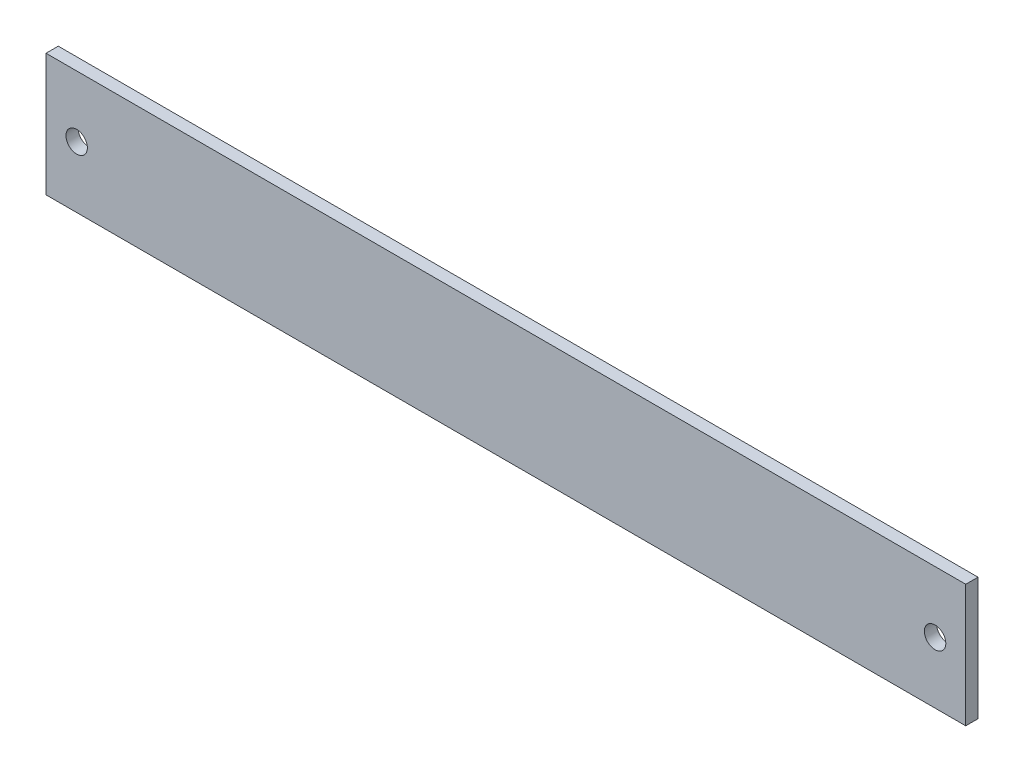
SolidWorks part; units mm, degrees
ref_plane "Front Plane" through (0, 0, 0) normal (0, 0, 1) x (1, 0, 0)
ref_plane "Top Plane" through (0, 0, 0) normal (0, 1, 0) x (1, 0, 0)
ref_plane "Right Plane" through (0, 0, 0) normal (1, 0, 0) x (0, 0, -1)
sketch "Sketch1" plane through (0, 0, 0) normal (0, 0, 1) x (1, 0, 0)
  line L1 (-75, -10) -> (75, -10)
  line L2 (-75, -10) -> (-75, 10)
  line L3 (-75, 10) -> (75, 10)
  line L4 (75, -10) -> (75, 10)
  line L5 (-75, -10) -> (75, 10) construction
  line L6 (-75, 10) -> (75, -10) construction
  point P0 (0, 0)
  dimension "D1" = 20
  dimension "D2" = 150
extrude "Boss-Extrude1" add sketch "Sketch1" along normal blind 2
sketch "Sketch2" plane through (0, 0, 2) normal (0, 0, 1) x (1, 0, 0)
  line L0 (0, 0) -> (93.1035, 0) construction
  line L1 (-75, 10) -> (-75, -10) construction
  line L2 (0, 0) -> (0, 26.3446) construction
  circle A0 centre (-70, 0) radius 1.75
  circle A1 centre (70, 0) radius 1.75
  dimension "D2" = 3.5
  dimension "D1" = 5
extrude "Cut-Extrude1" cut sketch "Sketch2" against normal up to next
